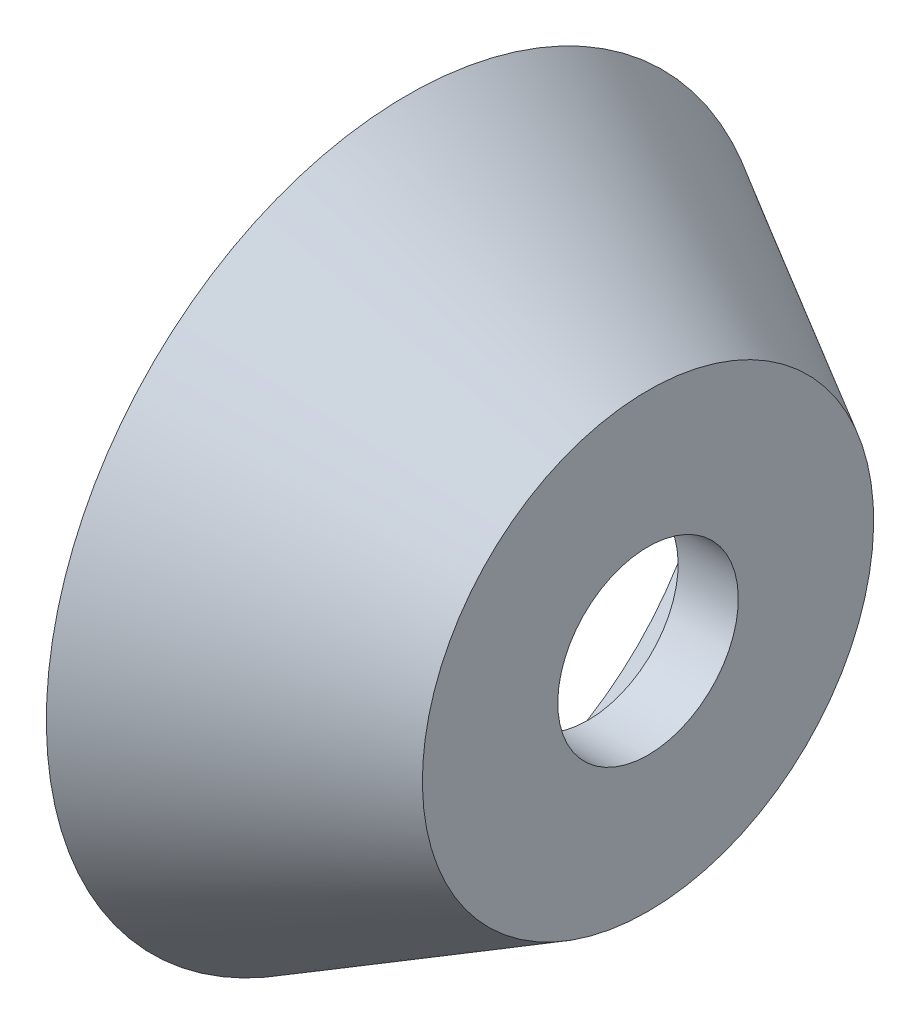
SolidWorks part; units mm, degrees
ref_plane "Front Plane" through (0, 0, 0) normal (0, 0, 1) x (1, 0, 0)
ref_plane "Top Plane" through (0, 0, 0) normal (0, 1, 0) x (1, 0, 0)
ref_plane "Right Plane" through (0, 0, 0) normal (1, 0, 0) x (0, 0, -1)
sketch "Sketch1" plane through (0, 0, 0) normal (0, 0, 1) x (1, 0, 0)
  line L0 (-6.35, 0) -> (6.35, 0) construction
  line L1 (3.175, 4.7625) -> (6.35, 4.7625)
  line L2 (6.35, 4.7625) -> (6.35, 11.9063)
  line L3 (6.35, 11.9063) -> (-6.35, 19.05)
  line L4 (-6.35, 19.05) -> (-4.2333, 14.2165)
  line L5 (-4.2333, 14.2165) -> (3.175, 10.0494)
  line L6 (3.175, 10.0494) -> (3.175, 4.7625)
  line L7 (-0.5292, 12.133) -> (1.0274, 14.9002) construction
  line L8 (6.35, 4.7625) -> (6.35, 19.05) construction
  line L9 (6.35, 11.9063) -> (-6.35, 19.05) construction
  dimension "Width" = 12.7
  dimension "OD" = 38.1
  dimension "ID" = 9.525
  dimension "Thickness" = 3.175
  dimension "D1" = 2.1167
revolve "Revolve1" add sketch "Sketch1" angle 360 about L0
equation "\"D1@Sketch1\"=\"Width@Sketch1\"/6"
